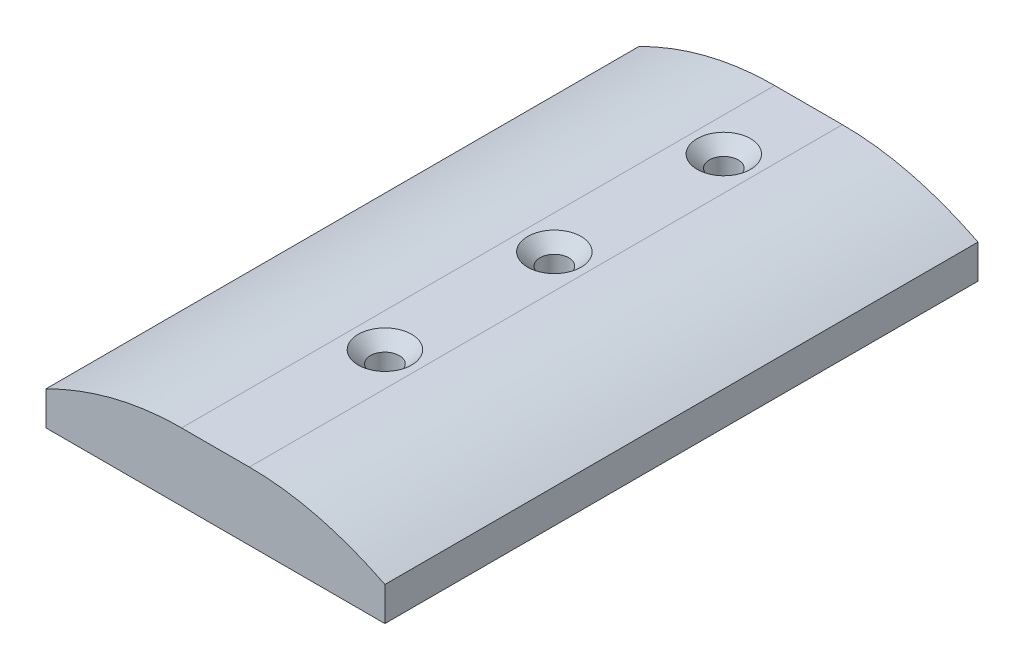
SolidWorks part; units mm, degrees
ref_plane "Front Plane" through (0, 0, 0) normal (0, 0, 1) x (1, 0, 0)
ref_plane "Top Plane" through (0, 0, 0) normal (0, 1, 0) x (1, 0, 0)
ref_plane "Right Plane" through (0, 0, 0) normal (1, 0, 0) x (0, 0, -1)
sketch "Sketch1" plane through (0, 0, 0) normal (0, 1, 0) x (1, 0, 0)
  line L0 (0, 35) -> (0, 25) construction
  line L1 (0, 25) -> (0, 5) construction
  line L2 (0, 5) -> (0, -15) construction
  line L3 (0, -15) -> (0, -35) construction
  line L4 (0, 35) -> (20, 35)
  line L5 (20, 35) -> (20, -35)
  line L6 (20, -35) -> (0, -35)
  line L7 (0, 35) -> (-20, 35)
  line L8 (-20, 35) -> (-20, -35)
  line L9 (-20, -35) -> (0, -35)
  circle A0 centre (0, 25) radius 1.25
  circle A1 centre (0, 5) radius 1.25
  circle A2 centre (0, -15) radius 1.25
extrude "Boss-Extrude1" add sketch "Sketch1" along normal blind 4
sketch "Sketch2" plane through (0, 0, -35) normal (0, 0, -1) x (-1, 0, 0)
  line L0 (0, 4) -> (0, 8) construction
  line L1 (-20, 4) -> (20, 4) construction
  line L2 (0, 8) -> (-4, 8)
  line L3 (-20, 4) -> (20, 4)
  line L4 (0, 8) -> (4, 8)
  spline S0 degree 3 poles (-4, 8) (-9.6522, 8) (-14.9845, 6.5139) (-20, 4) knots 0 0 0 0 1 1 1 1
  spline S1 degree 3 poles (4, 8) (9.6522, 8) (14.9845, 6.5139) (20, 4) knots 0 0 0 0 1 1 1 1
  dimension "D1" = 4
  dimension "D2" = 4
extrude "Boss-Extrude2" add sketch "Sketch2" against normal blind 70
sketch "Sketch3" plane through (0, 8, 0) normal (0, 1, 0) x (1, 0, 0)
  circle A0 centre (0, 25) radius 1.6
  circle A1 centre (0, 5) radius 1.6
  circle A2 centre (0, -15) radius 1.625
  dimension "D1" = 3.2
  dimension "D2" = 3.2
  dimension "D3" = 3.25
extrude "Cut-Extrude1" cut sketch "Sketch3" against normal blind 70
hole_wizard "CSK for M3 Flat Head Machine Screw1" positions "Sketch4" profile "Sketch5" countersink size "M3" standard "ANSI Metric" end condition through all
sketch "Sketch4" plane through (0, 8, 0) normal (0, 1, 0) x (1, 0, 0)
  point P0 (0, 25)
  point P3 (0, 5)
  point P6 (0, -15)
sketch "Sketch5" plane through (0, 8, -25) normal (1, 0, 0) x (0, 0, 1)
  line L0 (0, 0) -> (0, 8)
  line L1 (0, 8) -> (1.7, 8)
  line L2 (1.7, 8) -> (1.7, 1.45)
  line L3 (1.7, 1.45) -> (3.15, 0)
  line L5 (3.15, 0) -> (0, 0)
  line L6 (-1.7, 1.45) -> (-3.15, 0) construction
  line L11 (0, -6.35) -> (0, 107.95) construction
  dimension "Thru Hole Dia." = 3.4
  dimension "Thru Hole Depth" = 8
  dimension "Near C'Sink Dia." = 6.3
  dimension "Near C'Sink Angle" = 90
